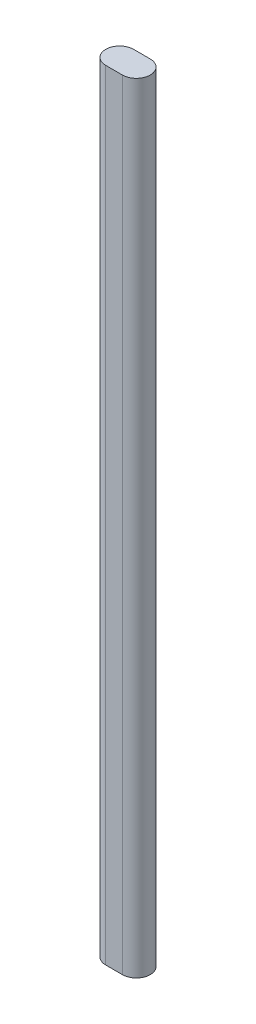
SolidWorks part; units mm, degrees
ref_plane "Alzado" through (0, 0, 0) normal (0, 0, 1) x (1, 0, 0)
ref_plane "Planta" through (0, 0, 0) normal (0, 1, 0) x (1, 0, 0)
ref_plane "Vista lateral" through (0, 0, 0) normal (1, 0, 0) x (0, 0, -1)
sketch "Croquis1" plane through (0, 0, 0) normal (0, 1, 0) x (1, 0, 0)
  line L0 (0, 0) -> (-15, 0) construction
  line L1 (0, -12.5) -> (-15, -12.5)
  line L2 (0, 12.5) -> (-15, 12.5)
  arc A0 (0, -12.5) -> (0, 12.5) centre (0, 0) ccw
  arc A1 (-15, 12.5) -> (-15, -12.5) centre (-15, 0) ccw
  point P3 (-7.5, 0)
  point P8 (-27.5, 0)
  point P9 (12.5, 0)
  point P10 (0, 0)
  dimension "D1" = 40
  dimension "D2" = 25
extrude "Saliente-Extruir1" add sketch "Croquis1" against normal blind 700
